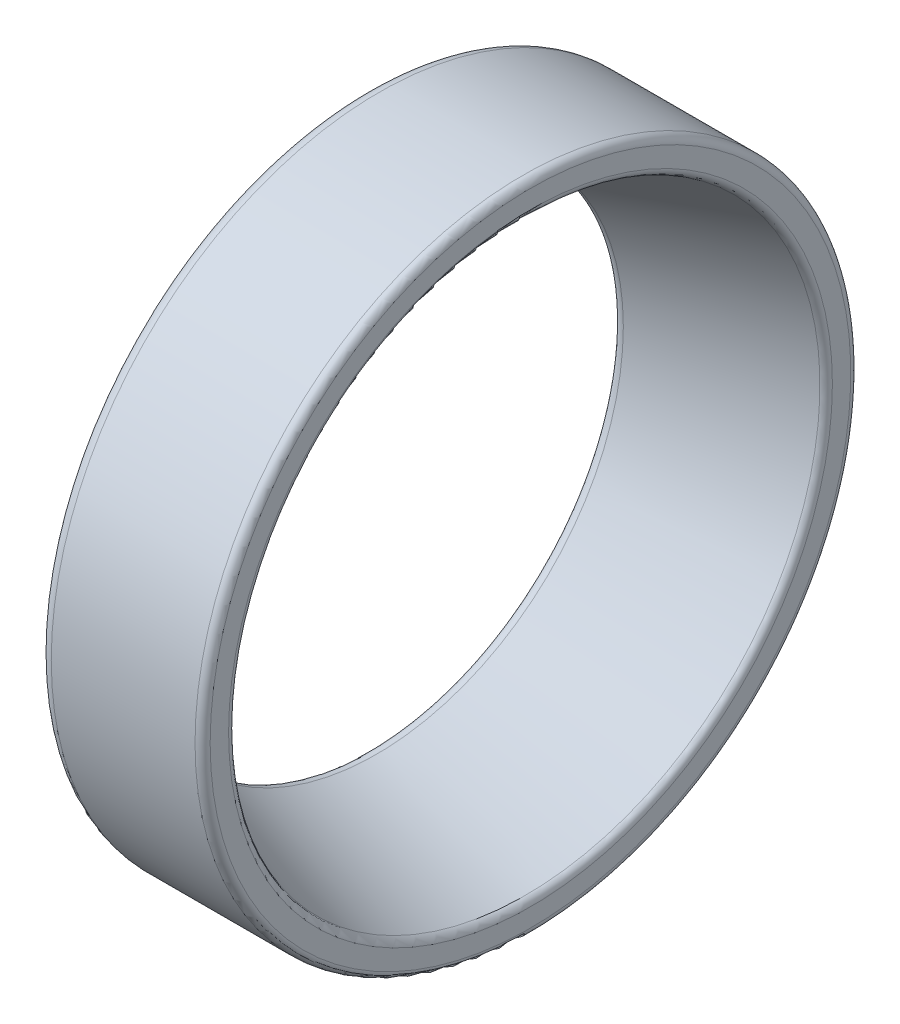
SolidWorks part; units mm, degrees
ref_plane "Plan1" through (0, 0, 0) normal (0, 0, 1) x (1, 0, 0)
ref_plane "Plan2" through (0, 0, 0) normal (0, 1, 0) x (1, 0, 0)
ref_plane "Plan3" through (0, 0, 0) normal (1, 0, 0) x (0, 0, -1)
sketch "Esquisse1" plane through (0, 0, 0) normal (0, 0, 1) x (1, 0, 0)
  line L0 (-15.2215, 26) -> (-3.8215, 26)
  line L1 (-3.2215, 25.4) -> (-3.2215, 23.9389)
  line L2 (-3.638, 23.3676) -> (-15.438, 19.5789)
  line L3 (-16.2215, 20.1501) -> (-16.2215, 25)
  line L4 (-17.9901, 0) -> (10.4363, 0) construction
  line L5 (-4.7217, 23.0197) -> (-14.2759, 19.952) construction
  line L6 (-3.671, 20.2087) -> (-13.7241, 17.4159) construction
  line L7 (-8.6976, 18.8123) -> (-3.4715, 0) construction
  line L8 (0, 0) -> (-86.5472, 0) construction
  arc A0 (-15.2215, 26) -> (-16.2215, 25) centre (-15.2215, 25) ccw
  arc A1 (-15.438, 19.5789) -> (-16.2215, 20.1501) centre (-15.6215, 20.1501) cw
  arc A2 (-3.2215, 23.9389) -> (-3.638, 23.3676) centre (-3.8215, 23.9389) cw
  arc A3 (-3.8215, 26) -> (-3.2215, 25.4) centre (-3.8215, 25.4) cw
  point P9 (-8.6976, 18.8123)
  point P22 (-3.2215, 23.5014)
  point P25 (-3.2215, 26)
  dimension "D4" = 1
  dimension "D6" = 0.6
  dimension "D1" = 13
  dimension "D2" = 26
  dimension "D3" = 12.75
  dimension "D5" = 2.4986
revolve "Base-Révolution" add sketch "Esquisse1" angle 360 about L4
